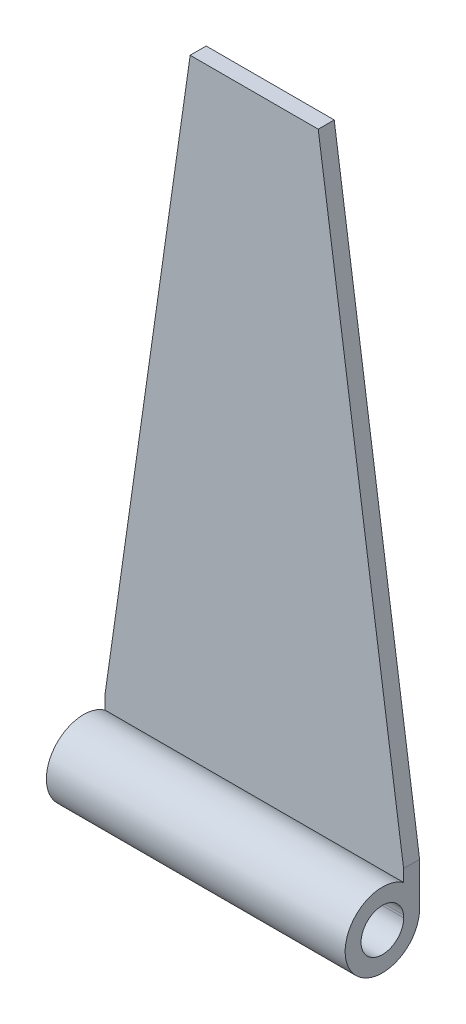
SolidWorks part; units mm, degrees
material "Plain Carbon Steel"
ref_plane "Front Plane" through (0, 0, 0) normal (0, 0, 1) x (1, 0, 0)
ref_plane "Top Plane" through (0, 0, 0) normal (0, 1, 0) x (1, 0, 0)
ref_plane "Right Plane" through (0, 0, 0) normal (1, 0, 0) x (0, 0, -1)
sketch "Sketch1" plane through (0, 0, 0) normal (0, 0, 1) x (1, 0, 0)
  line L0 (-11.1125, -20.6375) -> (-4.7625, 23.8125)
  line L1 (-4.7625, 23.8125) -> (4.7625, 23.8125)
  line L2 (4.7625, 23.8125) -> (11.1125, -20.6375)
  line L3 (-11.1125, -20.6375) -> (-11.1125, -23.8125)
  line L4 (0, 23.8125) -> (0, -23.8125) construction
  line L5 (-11.1125, -23.8125) -> (11.1125, -23.8125)
  line L6 (11.1125, -23.8125) -> (11.1125, -20.6375)
  point P6 (0, 0)
  dimension "D1" = 47.625
  dimension "D2" = 9.525
  dimension "D3" = 22.225
  dimension "D4" = 3.175
extrude "Boss-Extrude1" add sketch "Sketch1" along normal mid plane 1.1906
sketch "Sketch2" plane through (0, 0, 0) normal (1, 0, 0) x (0, 0, -1)
  circle A0 centre (-2.1733, -23.8125) radius 2.7686
  circle A1 centre (-2.1733, -23.8125) radius 1.5875
  dimension "D1" = 3.175
  dimension "D2" = 5.5372
extrude "Boss-Extrude2" add sketch "Sketch2" along normal mid plane 22.225
